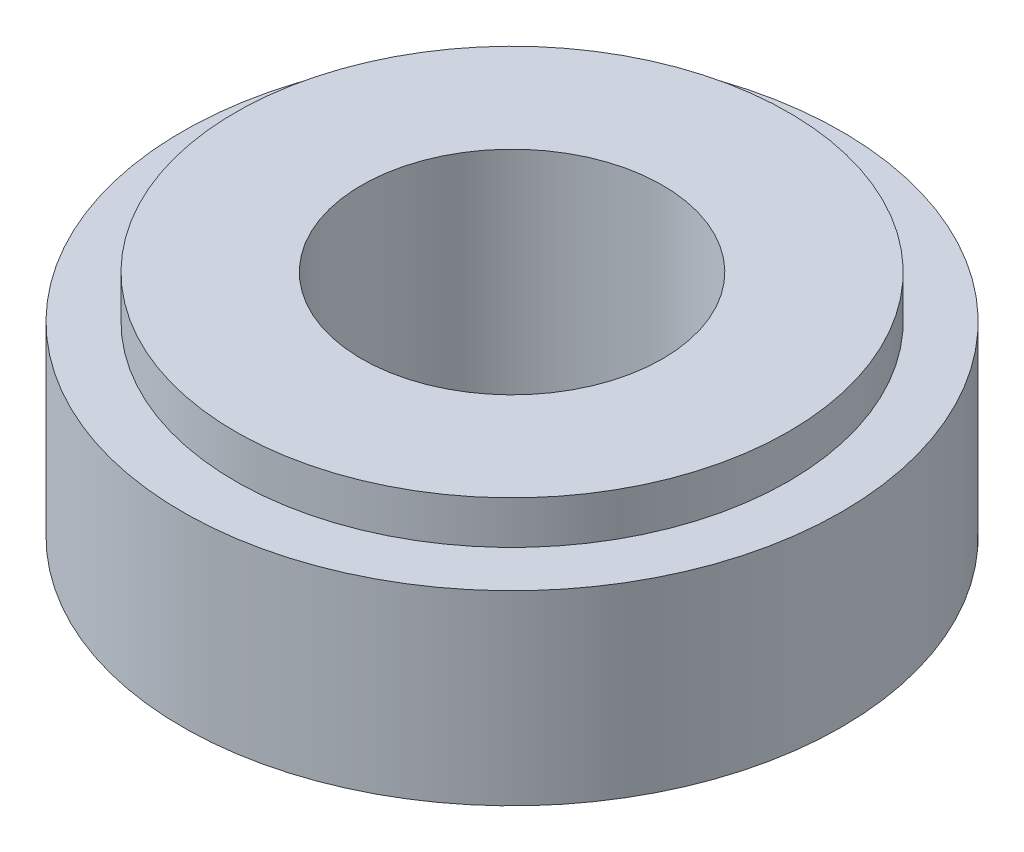
SolidWorks part; units mm, degrees
ref_plane "Front Plane" through (0, 0, 0) normal (0, 0, 1) x (1, 0, 0)
ref_plane "Top Plane" through (0, 0, 0) normal (0, 1, 0) x (1, 0, 0)
ref_plane "Right Plane" through (0, 0, 0) normal (1, 0, 0) x (0, 0, -1)
sketch "Sketch1" plane through (0, 0, 0) normal (0, 0, 1) x (1, 0, 0)
  line L0 (0, -126.6229) -> (0, 6204.5202) construction
  line L1 (-2.625, 0) -> (-5.75, 0)
  line L2 (-5.75, 0) -> (-5.75, 3.25)
  line L3 (-5.75, 3.25) -> (-4.825, 3.25)
  line L4 (-4.825, 3.25) -> (-4.825, 4)
  line L5 (-4.825, 4) -> (-2.625, 4)
  line L6 (-2.625, 4) -> (-2.625, 0)
  point P1 (0, 0)
  point P5 (-6.2633, 2.8972)
  dimension "D1" = 4
  dimension "D2" = 9.65
  dimension "D3" = 11.5
  dimension "D4" = 0.75
  dimension "D5" = 5.25
revolve "Revolve1" add sketch "Sketch1" angle 360 about L0
equation "\"D2@Sketch1\"=9.9mm-0.25mm"
equation "\"D4@Sketch1\"=1mm-0.25"
equation "\"D5@Sketch1\"=5mm+0.25mm"
